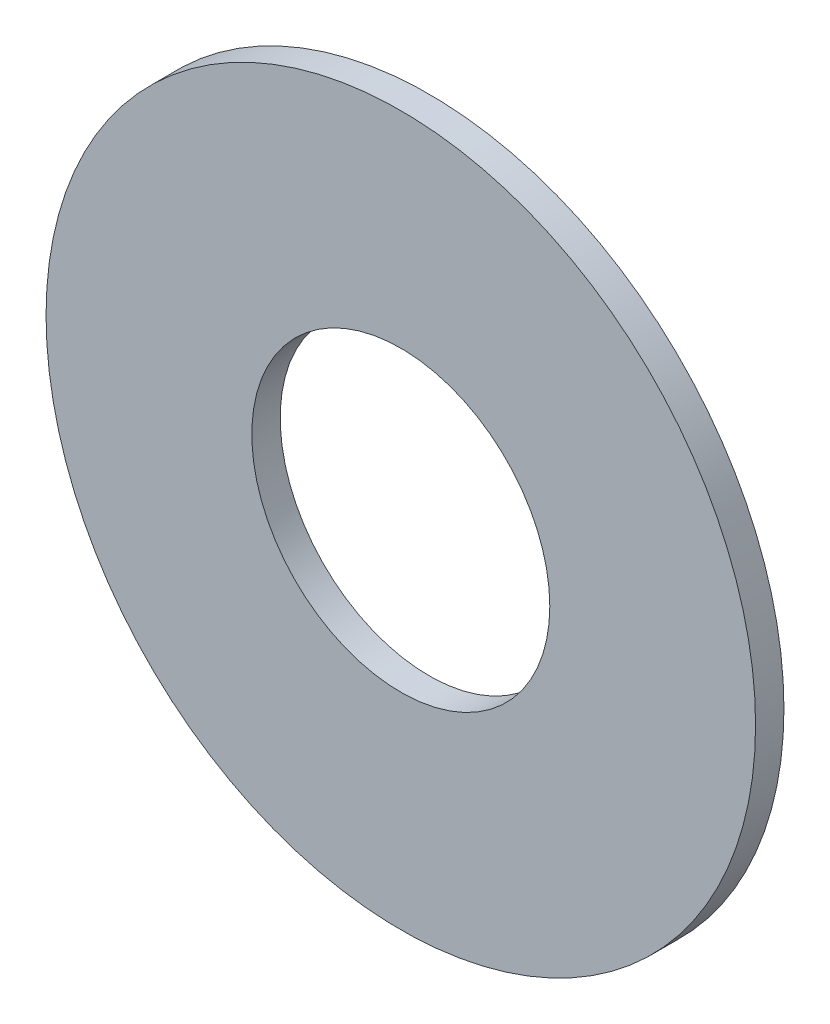
SolidWorks part; units mm, degrees
material "PTFE (general)"
ref_plane "Front" through (0, 0, 0) normal (0, 0, 1) x (1, 0, 0)
ref_plane "Top" through (0, 0, 0) normal (0, 1, 0) x (1, 0, 0)
ref_plane "Right" through (0, 0, 0) normal (1, 0, 0) x (0, 0, -1)
sketch "GasketSke" plane through (0, 0, 0) normal (0, 0, 1) x (1, 0, 0)
  circle A0 centre (0, 0) radius 2.5
  circle A1 centre (0, 0) radius 1.05
  dimension "D1" = 2.1
  dimension "D2" = 5
extrude "Gasket" add sketch "GasketSke" along normal blind 0.2
